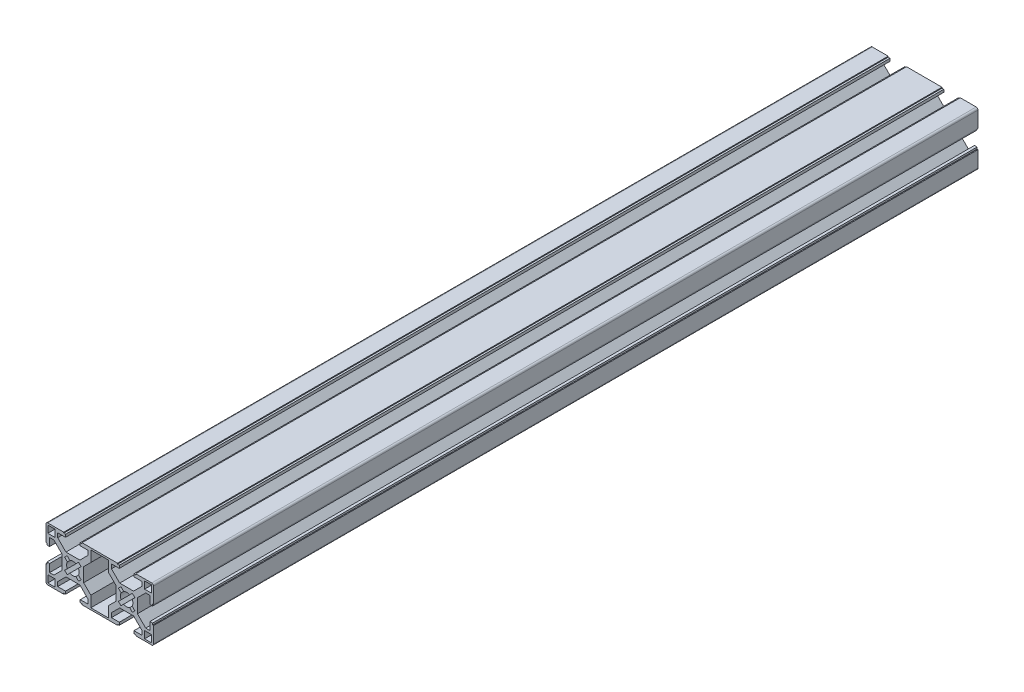
SolidWorks part; units mm, degrees
material "6063-T83"
ref_plane "Plano frontal" through (0, 0, 0) normal (0, 0, 1) x (1, 0, 0)
ref_plane "Plano superior" through (0, 0, 0) normal (0, 1, 0) x (1, 0, 0)
ref_plane "Plano direito" through (0, 0, 0) normal (1, 0, 0) x (0, 0, -1)
sketch "Esboço1" plane through (0, 0, 0) normal (0, 0, 1) x (1, 0, 0)
  line L5 (0, 0) -> (-17.7944, 17.7944) construction
  line L6 (0, 3.5) -> (0, 6)
  line L8 (0, 6) -> (-3.8787, 6)
  line L9 (-3.5, 0) -> (-6, 0)
  line L48 (-6, 0) -> (-6, 3.8787)
  line L49 (-3.8787, 6) -> (-8.5, 10.6213)
  line L50 (-6, 3.8787) -> (-10.6213, 8.5)
  line L51 (0, 0) -> (-12.921, 0) construction
  line L52 (-8.5, 13) -> (-4.1, 13)
  line L53 (-4.1, 13) -> (-4.1, 14.5)
  line L54 (-4.1, 14.5) -> (-5.1, 14.5)
  line L55 (-5.1, 14.5) -> (-5.1, 15)
  line L56 (-5.1, 15) -> (-15, 15)
  line L57 (-15, 5.1) -> (-15, 15)
  line L58 (-14.5, 5.1) -> (-15, 5.1)
  line L59 (-14.5, 4.1) -> (-14.5, 5.1)
  line L60 (-13, 4.1) -> (-14.5, 4.1)
  line L61 (-13, 8.5) -> (-13, 4.1)
  line L62 (-1.6646, 3.0788) -> (-3.182, 4.5962)
  line L63 (-3.0788, 1.6646) -> (-4.5962, 3.182)
  line L64 (-4.5962, 3.182) -> (-3.182, 4.5962)
  line L65 (-8.5, 13) -> (-8.5, 10.6213)
  line L66 (-10, 14) -> (-14, 14)
  line L67 (-10, 14) -> (-10, 10)
  line L68 (-10, 10) -> (-14, 10)
  line L69 (-14, 14) -> (-14, 10)
  line L70 (-10, 14) -> (-14, 10) construction
  line L71 (-10, 10) -> (-14, 14) construction
  line L72 (-13, 8.5) -> (-10.6213, 8.5)
  circle A1 centre (0, 0) radius 3.5
  point P25 (-12, 12)
  dimension "D5" = 10.9
  dimension "D9" = 5.5
  dimension "D10" = 2
  dimension "D11" = 4
  dimension "D12" = 4
  dimension "D13" = 1
  dimension "D1" = 7
  dimension "D2" = 6
  dimension "D3" = 3
  dimension "D4" = 9.9
  dimension "D6" = 0.5
  dimension "D7" = 1.5
  dimension "D8" = 15
  dimension "D14" = 6.5
extrude "Ressalto-extrusão1" add sketch "Esboço1" along normal blind 460 contours A1 L6 L8 L49 L65 L52 L53 L54 L55 L56 L57 L58 L59 L60 L61 L72 L50 L48 L9 L63 L64 L62 L69 L66 L67 L68
sketch "Esboço3" plane through (0, 0, 0) normal (1, 0, 0) x (0, 0, -1)
  line L0 (0, 0) -> (-1000, 0) construction
  dimension "D1" = 1000
pattern_circular "PadrãoCircular1" count 4 every 90 about axis through (0, 0, 0) along (0, 0, 1) of "Ressalto-extrusão1"
pattern_linear "Padrão linear1" count 2 spacing 30 along (1, 0, 0) of "Ressalto-extrusão1", "PadrãoCircular1"
sketch "Esboço4" plane through (0, 0, 0) normal (0, 0, -1) x (-1, 0, 0)
  line L0 (-20, 14) -> (-20, -14)
  line L1 (-20, -14) -> (-10, -14)
  line L2 (-10, -14) -> (-10, 14)
  line L3 (-10, 14) -> (-20, 14)
extrude "Corte-extrusão1" cut sketch "Esboço4" against normal through all
fillet "Filete1" radius 1 4 edges at (45, -15, 230) (45, 15, 230) (-15, 15, 230) (-15, -15, 230)
ref_plane "Plane1" through (0, 0, 230) normal (0, 0, -1) x (-1, 0, 0)
ref_plane "Plane2" through (15, 0, 0) normal (-1, 0, 0) x (0, 0, 1)
